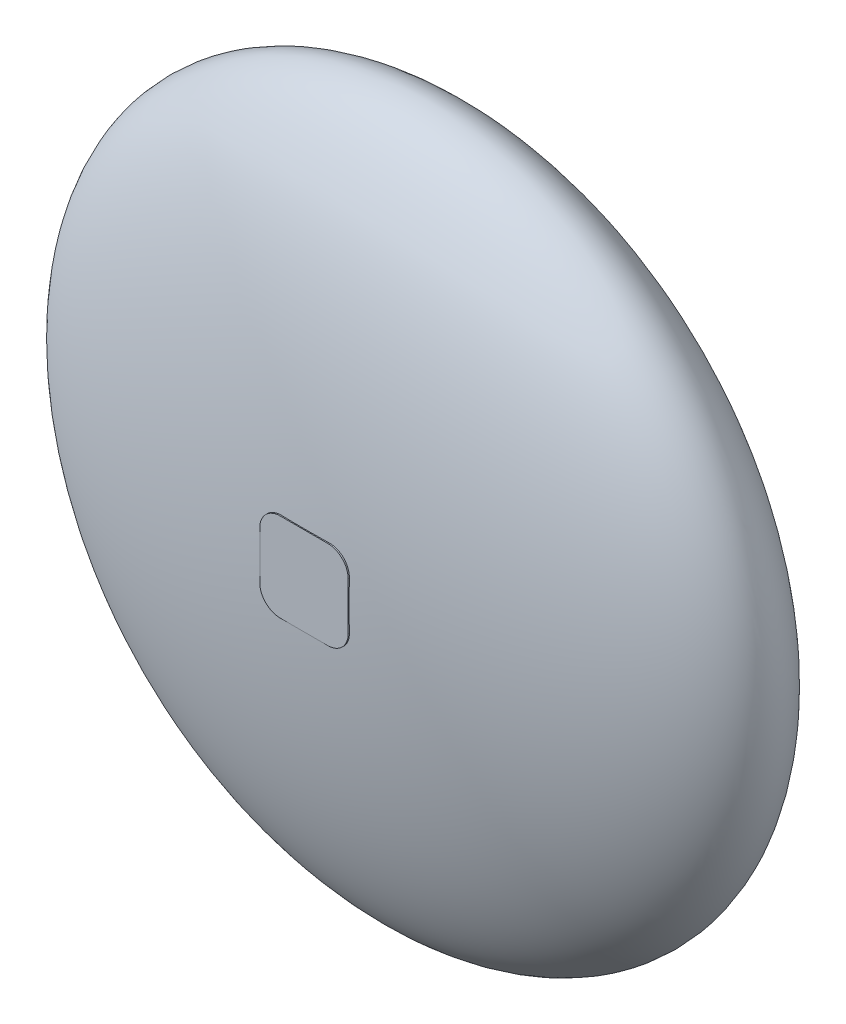
SolidWorks part; units mm, degrees
ref_plane "Front Plane" through (0, 0, 0) normal (0, 0, 1) x (1, 0, 0)
ref_plane "Top Plane" through (0, 0, 0) normal (0, 1, 0) x (1, 0, 0)
ref_plane "Right Plane" through (0, 0, 0) normal (1, 0, 0) x (0, 0, -1)
other "Center of Mass"
sketch "Sketch1" plane through (0, 0, 0) normal (0, 1, 0) x (1, 0, 0)
  line L0 (0, 17.5) -> (0, -17.5) construction
  line L1 (0, 17.5) -> (0, -17.5)
  ellipse E0 centre (0, 0) end of major axis (-52.5, 0) minor radius 17.5 (0, -17.5) -> (0, 17.5) ccw
  dimension "D1" = 17.5
  dimension "D2" = 52.5
revolve "Revolve4" add sketch "Sketch1" angle 360 about L0
sketch "Sketch2" plane through (0, 0, 0) normal (0, 0, 1) x (1, 0, 0)
  line L1 (6.5, -6.5) -> (-6.5, -6.5)
  line L2 (6.5, -6.5) -> (6.5, 6.5)
  line L3 (6.5, 6.5) -> (-6.5, 6.5)
  line L4 (-6.5, -6.5) -> (-6.5, 6.5)
  line L5 (6.5, -6.5) -> (-6.5, 6.5) construction
  line L6 (6.5, 6.5) -> (-6.5, -6.5) construction
  point P0 (0, 0)
  dimension "D1" = 13
extrude "Boss-Extrude1" add sketch "Sketch2" along normal through all
fillet "Fillet1" radius 3 4 edges at (6.5, -6.5, 17.3648) (-6.5, 6.5, 17.3648) (6.5, 6.5, 17.3648) (-6.5, -6.5, 17.3648)
ref_plane "Plane1" through (0, 0, 8) normal (0, 0, 1) x (1, 0, 0)
sketch "Sketch3" plane through (0, 0, 8) normal (0, 0, 1) x (1, 0, 0)
  circle A0 centre (0, 14) radius 4.6
  circle A1 centre (10.9456, 8.7289) radius 4.6
  circle A2 centre (13.649, -3.1153) radius 4.6
  circle A3 centre (6.0744, -12.6136) radius 4.6
  circle A4 centre (-6.0744, -12.6136) radius 4.6
  circle A5 centre (-13.649, -3.1153) radius 4.6
  circle A6 centre (-10.9456, 8.7289) radius 4.6
  circle A7 centre (0, 0) radius 7
  point P19 (0, 0)
  dimension "D1" = 9.2
  dimension "D4" = 14
  dimension "D2" = 14
  dimension "D3" = 7
extrude "Cut-Extrude1" cut sketch "Sketch3" against normal blind 16
